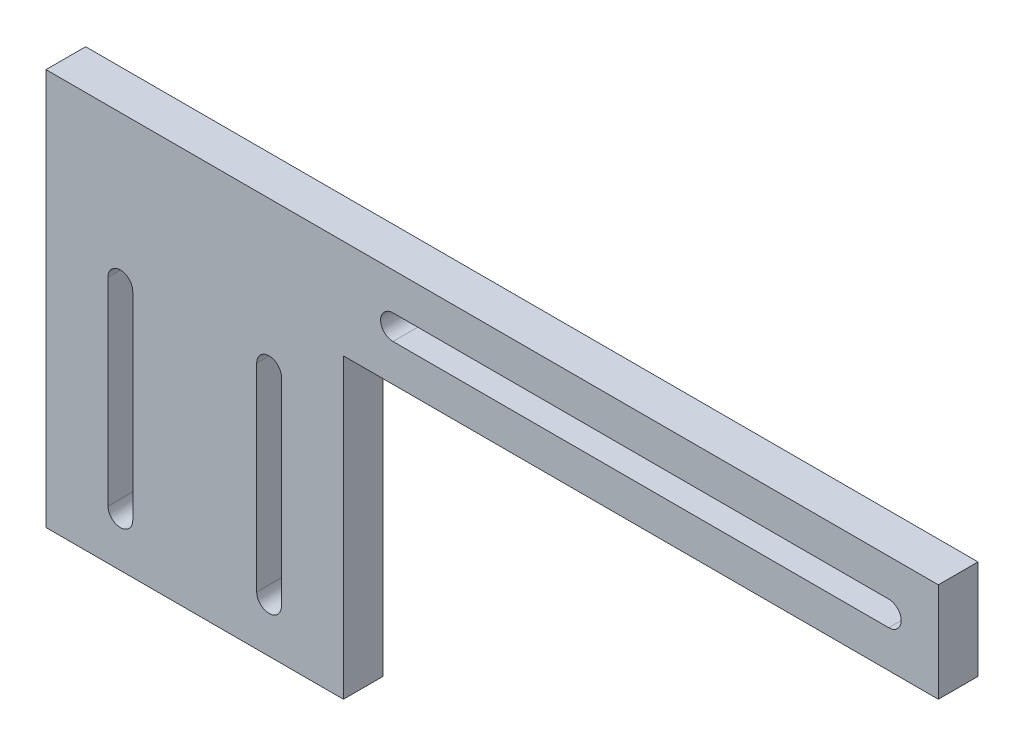
SolidWorks part; units mm, degrees
material "Plain Carbon Steel"
ref_plane "Front Plane" through (0, 0, 0) normal (0, 0, 1) x (1, 0, 0)
ref_plane "Top Plane" through (0, 0, 0) normal (0, 1, 0) x (1, 0, 0)
ref_plane "Right Plane" through (0, 0, 0) normal (1, 0, 0) x (0, 0, -1)
sketch "Sketch1" plane through (0, 0, 0) normal (0, 0, 1) x (1, 0, 0)
  line L0 (0, 0) -> (38.1, 0)
  line L1 (38.1, 0) -> (38.1, 38.1)
  line L2 (38.1, 38.1) -> (114.3, 38.1)
  line L3 (114.3, 38.1) -> (114.3, 50.8)
  line L4 (114.3, 50.8) -> (0, 50.8)
  line L5 (0, 50.8) -> (0, 0)
  line L6 (9.525, 6.35) -> (9.525, 31.75) construction
  line L7 (7.9375, 6.35) -> (7.9375, 31.75)
  line L8 (11.1125, 6.35) -> (11.1125, 31.75)
  line L9 (28.575, 31.75) -> (28.575, 6.35) construction
  line L10 (30.1625, 31.75) -> (30.1625, 6.35)
  line L11 (26.9875, 31.75) -> (26.9875, 6.35)
  line L12 (28.575, 19.05) -> (9.525, 19.05) construction
  line L13 (107.95, 44.45) -> (44.45, 44.45) construction
  line L14 (107.95, 42.8625) -> (44.45, 42.8625)
  line L15 (107.95, 46.0375) -> (44.45, 46.0375)
  line L16 (28.575, 4.7625) -> (28.575, 0) construction
  line L17 (109.5375, 44.45) -> (114.3, 44.45) construction
  arc A0 (7.9375, 6.35) -> (11.1125, 6.35) centre (9.525, 6.35) ccw
  arc A1 (11.1125, 31.75) -> (7.9375, 31.75) centre (9.525, 31.75) ccw
  arc A2 (30.1625, 31.75) -> (26.9875, 31.75) centre (28.575, 31.75) ccw
  arc A3 (26.9875, 6.35) -> (30.1625, 6.35) centre (28.575, 6.35) ccw
  arc A4 (107.95, 42.8625) -> (107.95, 46.0375) centre (107.95, 44.45) ccw
  arc A5 (44.45, 46.0375) -> (44.45, 42.8625) centre (44.45, 44.45) ccw
  point P9 (9.525, 19.05)
  point P14 (28.575, 19.05)
  point P23 (19.05, 19.05)
  point P24 (19.05, 0)
  point P25 (38.1, 19.05)
  point P28 (76.2, 44.45)
  point P33 (114.3, 44.45)
  point P34 (76.2, 38.1)
  dimension "D7" = 3.175
  dimension "D1" = 38.1
  dimension "D2" = 38.1
  dimension "D3" = 50.8
  dimension "D4" = 114.3
  dimension "D5" = 25.4
  dimension "D6" = 19.05
extrude "Boss-Extrude2" add sketch "Sketch1" along normal blind 5.08
